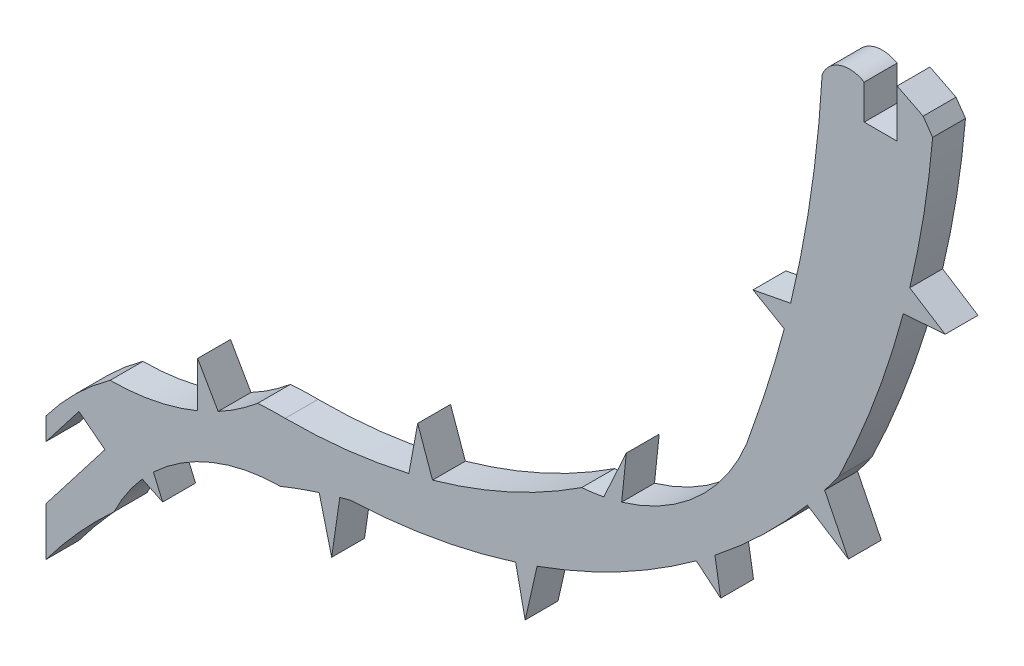
SolidWorks part; units mm, degrees
ref_plane "Front Plane" through (0, 0, 0) normal (0, 0, 1) x (1, 0, 0)
ref_plane "Top Plane" through (0, 0, 0) normal (0, 1, 0) x (1, 0, 0)
ref_plane "Right Plane" through (0, 0, 0) normal (1, 0, 0) x (0, 0, -1)
sketch "Sketch1" plane through (0, 0, 0) normal (0, 0, 1) x (1, 0, 0)
  line L0 (0, 36.7667) -> (1.524, 36.7667)
  line L1 (1.524, 36.7667) -> (1.524, 38.9826)
  line L2 (1.524, 38.9826) -> (2.7331, 38.3752)
  line L3 (2.7331, 38.3752) -> (3.1732, 37.7404)
  line L4 (-37.9325, 6.0109) -> (-37.9343, 4.9771)
  line L5 (0, 36.7667) -> (0, 38.3752)
  line L6 (-37.9365, 3.7282) -> (-35.812, 6.4769) construction
  line L7 (-37.9387, 2.4793) -> (-35.2091, 6.0109)
  line L8 (-37.9343, 4.9771) -> (-36.4149, 6.9429)
  line L9 (2.1116, 31.1694) -> (3.7521, 30.1224)
  line L10 (-35.2091, 6.0109) -> (-36.4149, 6.9429)
  line L11 (-37.9387, 2.4793) -> (-37.9427, 0.2321)
  line L12 (3.7521, 30.1224) -> (1.8115, 29.9823)
  line L14 (-1.8333, 21.0705) -> (-0.7325, 18.852)
  line L15 (-0.7325, 18.852) -> (-2.6381, 20.068)
  line L16 (-3.4122, 27.7873) -> (-5.1572, 27.4531)
  line L17 (-5.1572, 27.4531) -> (-3.7085, 26.6155)
  line L18 (-6.9228, 15.9133) -> (-6.6576, 14.3184)
  line L19 (-6.6576, 14.3184) -> (-7.7879, 15.257)
  line L20 (-11.2493, 15.8807) -> (-11.0311, 17.9622)
  line L21 (-11.0311, 17.9622) -> (-12.0765, 15.6798)
  line L22 (-16.1643, 11.0136) -> (-15.7234, 8.9125)
  line L23 (-15.7234, 8.9125) -> (-15.1693, 11.3493)
  line L24 (-20.0195, 12.3814) -> (-20.7064, 14.3184)
  line L25 (-20.7064, 14.3184) -> (-21.116, 12.0989)
  line L26 (-25.2761, 9.2537) -> (-24.6957, 6.9429)
  line L27 (-24.6957, 6.9429) -> (-24.3195, 9.5385)
  line L28 (-29.9598, 10.1697) -> (-30.9106, 11.8237)
  line L29 (-30.9106, 11.8237) -> (-30.9106, 9.72)
  line L30 (-32.9625, 6.2317) -> (-32.5322, 5.2439)
  line L31 (-32.5322, 5.2439) -> (-33.4807, 5.694)
  arc A0 (0, 38.3752) -> (-1.9515, 37.7033) centre (-0.6841, 37.1923) ccw
  arc A1 (-1.9515, 37.7033) -> (-3.4122, 27.7873) centre (-57.2758, 40.7874) cw
  arc A2 (3.1732, 37.7404) -> (2.1116, 31.1694) centre (-41.7442, 41.6258) cw
  arc A3 (-1.1675, 21.9739) -> (-1.8333, 21.0705) centre (-24.9991, 38.8422) cw
  arc A4 (-23.832, 9.6682) -> (-24.3195, 9.5385) centre (-17.5241, -15.0331) ccw
  arc A5 (-5.1572, 21.9739) -> (-11.2493, 15.8807) centre (-13.782, 24.505) cw
  arc A6 (-26.8528, 11.447) -> (-28.132, 11.4078) centre (-27.0783, -2.1026) ccw
  arc A7 (-34.7856, 3.7282) -> (-33.4807, 5.694) centre (-27.03, -0.0036) cw
  arc A8 (-34.7856, 3.7282) -> (-37.9427, 0.2321) centre (-17.5241, -15.0331) ccw
  arc A9 (-26.8528, 11.447) -> (-21.116, 12.0989) centre (-26.7744, 36.325) ccw
  arc A10 (-34.9719, 8.9125) -> (-30.9106, 9.72) centre (-34.9739, 19.5401) ccw
  arc A11 (-34.9719, 8.9125) -> (-37.9325, 6.0109) centre (-27.0783, -2.1026) ccw
  arc A12 (-32.9625, 6.2317) -> (-27.0783, 8.6029) centre (-27.03, -0.0036) cw
  arc A13 (-29.9598, 10.1697) -> (-28.132, 11.4078) centre (-34.9739, 19.5401) ccw
  arc A14 (-25.2761, 9.2537) -> (-27.0783, 8.6029) centre (-17.5241, -15.0331) ccw
  arc A15 (-20.0195, 12.3814) -> (-13.0993, 15.5424) centre (-26.7744, 36.325) ccw
  arc A16 (-16.1643, 11.0136) -> (-23.832, 9.6682) centre (-24.9991, 38.8422) cw
  arc A17 (-12.0765, 15.6798) -> (-13.0993, 15.5424) centre (-13.782, 24.505) cw
  arc A18 (-7.7879, 15.257) -> (-15.1693, 11.3493) centre (-24.9991, 38.8422) cw
  arc A19 (-2.6381, 20.068) -> (-6.9228, 15.9133) centre (-24.9991, 38.8422) cw
  arc A20 (1.8115, 29.9823) -> (-1.1675, 21.9739) centre (-41.7442, 41.6258) cw
  arc A21 (-3.7085, 26.6155) -> (-5.1572, 21.9739) centre (-57.2758, 40.7874) cw
  point P29 (-34.0422, 5.2051)
  point P30 (-31.9177, 7.9538)
extrude "Boss-Extrude1" add sketch "Sketch1" along normal blind 1.524
